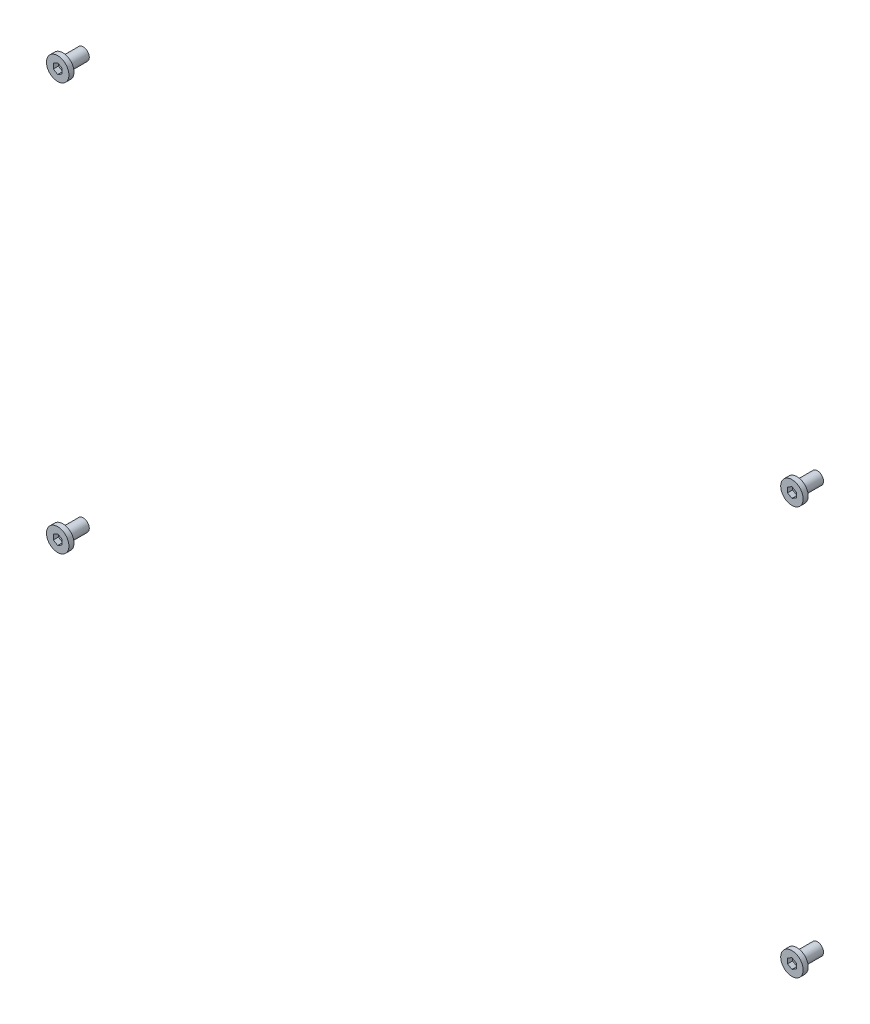
SolidWorks part; units mm, degrees
ref_plane "Спереди" through (0, 0, 0) normal (0, 0, 1) x (1, 0, 0)
ref_plane "Сверху" through (0, 0, 0) normal (0, 1, 0) x (1, 0, 0)
ref_plane "Справа" through (0, 0, 0) normal (1, 0, 0) x (0, 0, -1)
sketch "Эскиз1" plane through (0, 0, 0) normal (0, 0, 1) x (1, 0, 0)
  line L1 (-36, 20) -> (36, 20) construction
  line L2 (-36, 20) -> (-36, -20) construction
  line L3 (-36, -20) -> (36, -20) construction
  line L4 (36, 20) -> (36, -20) construction
  line L5 (-36, 20) -> (36, -20) construction
  line L6 (-36, -20) -> (36, 20) construction
  circle A0 centre (-36, 20) radius 0.6
  circle A1 centre (36, 20) radius 0.6
  circle A2 centre (36, -20) radius 0.6
  circle A3 centre (-36, -20) radius 0.6
  point P0 (0, 0)
  dimension "D3" = 1.2
  dimension "D1" = 72
  dimension "D2" = 40
extrude "Бобышка-Вытянуть1" add sketch "Эскиз1" along normal blind 2
sketch "Эскиз2" plane through (0, 0, 2) normal (0, 0, 1) x (1, 0, 0)
  circle A0 centre (-36, 20) radius 1.1
  circle A1 centre (36, 20) radius 1.1
  circle A2 centre (36, -20) radius 1.1
  circle A3 centre (-36, -20) radius 1.1
  dimension "D1" = 2.2
extrude "Бобышка-Вытянуть2" add sketch "Эскиз2" along normal blind 0.5
sketch "Эскиз3" plane through (0, 0, 2.5) normal (0, 0, 1) x (1, 0, 0)
  line L1 (36.433, -20.25) -> (36.433, -19.75)
  line L2 (36.433, -19.75) -> (36, -19.5)
  line L3 (36, -19.5) -> (35.567, -19.75)
  line L4 (35.567, -19.75) -> (35.567, -20.25)
  line L5 (35.567, -20.25) -> (36, -20.5)
  line L6 (36, -20.5) -> (36.433, -20.25)
  line L7 (36.433, 19.75) -> (36.433, 20.25)
  line L8 (36.433, 20.25) -> (36, 20.5)
  line L9 (36, 20.5) -> (35.567, 20.25)
  line L10 (35.567, 20.25) -> (35.567, 19.75)
  line L11 (35.567, 19.75) -> (36, 19.5)
  line L12 (36, 19.5) -> (36.433, 19.75)
  line L13 (-35.567, 19.75) -> (-35.567, 20.25)
  line L14 (-35.567, 20.25) -> (-36, 20.5)
  line L15 (-36, 20.5) -> (-36.433, 20.25)
  line L16 (-36.433, 20.25) -> (-36.433, 19.75)
  line L17 (-36.433, 19.75) -> (-36, 19.5)
  line L18 (-36, 19.5) -> (-35.567, 19.75)
  line L19 (-35.567, -20.25) -> (-35.567, -19.75)
  line L20 (-35.567, -19.75) -> (-36, -19.5)
  line L21 (-36, -19.5) -> (-36.433, -19.75)
  line L22 (-36.433, -19.75) -> (-36.433, -20.25)
  line L23 (-36.433, -20.25) -> (-36, -20.5)
  line L24 (-36, -20.5) -> (-35.567, -20.25)
  circle A0 centre (36, -20) radius 0.433 construction
  circle A1 centre (36, 20) radius 0.433 construction
  circle A2 centre (-36, 20) radius 0.433 construction
  circle A3 centre (-36, -20) radius 0.433 construction
  dimension "D1" = 0.5
extrude "Вырез-Вытянуть1" cut sketch "Эскиз3" against normal blind 0.5
